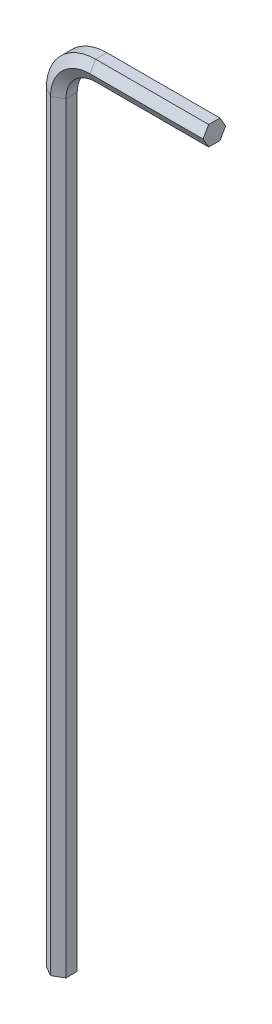
SolidWorks part; units mm, degrees
other "Defeature"
material "Plain Carbon Steel"
ref_plane "Front Plane" through (0, 0, 0) normal (0, 0, 1) x (1, 0, 0)
ref_plane "Top Plane" through (0, 0, 0) normal (0, 1, 0) x (1, 0, 0)
ref_plane "Right Plane" through (0, 0, 0) normal (1, 0, 0) x (0, 0, -1)
sketch "Sketch1" plane through (0, 0, 0) normal (0, 0, 1) x (1, 0, 0)
  line L0 (0, 0) -> (0, 77.2094)
  line L1 (4, 81.2094) -> (15.4694, 81.2094)
  arc A0 (0, 77.2094) -> (4, 81.2094) centre (4, 77.2094) cw
  point P8 (0, 81.2094)
  dimension "D4" = 4
  dimension "D1" = 81.2094
  dimension "D3" = 15.4694
sketch "Sketch2" plane through (0, 0, 0) normal (0, 1, 0) x (1, 0, 0)
  line L1 (-0.9906, 0.5719) -> (-0.9906, -0.5719)
  line L2 (-0.9906, -0.5719) -> (0, -1.1438)
  line L3 (0, -1.1438) -> (0.9906, -0.5719)
  line L4 (0.9906, -0.5719) -> (0.9906, 0.5719)
  line L5 (0.9906, 0.5719) -> (0, 1.1438)
  line L6 (0, 1.1438) -> (-0.9906, 0.5719)
  circle A0 centre (0, 0) radius 0.9906 construction
  dimension "D1" = 1.9812
sweep "Sweep1" add profiles "Sketch2" path "Sketch1"
